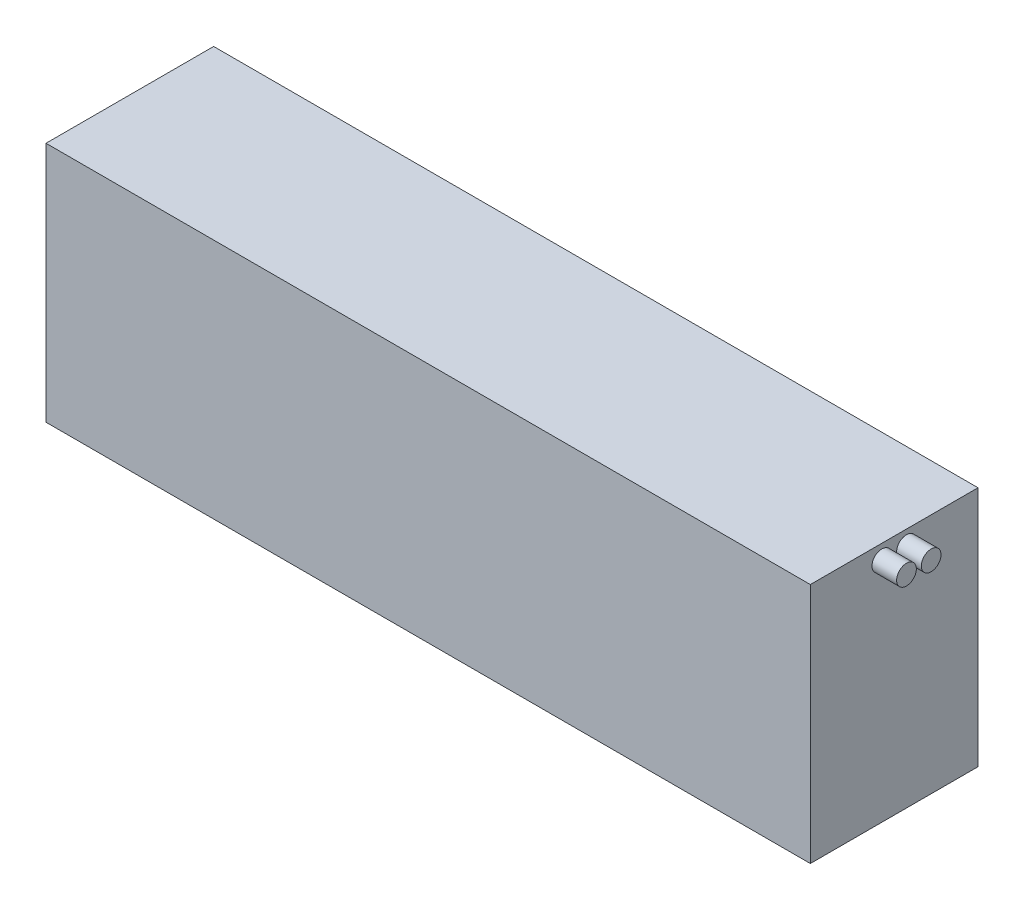
SolidWorks part; units mm, degrees
ref_plane "Plan de face" through (0, 0, 0) normal (0, 0, 1) x (1, 0, 0)
ref_plane "Plan de dessus" through (0, 0, 0) normal (0, 1, 0) x (1, 0, 0)
ref_plane "Plan de droite" through (0, 0, 0) normal (1, 0, 0) x (0, 0, -1)
sketch "Esquisse1" plane through (0, 0, 0) normal (0, 1, 0) x (1, 0, 0)
  line L1 (0, 0) -> (155, 0)
  line L2 (0, 0) -> (0, 34)
  line L3 (0, 34) -> (155, 34)
  line L4 (155, 0) -> (155, 34)
  dimension "D1" = 34
  dimension "D2" = 155
extrude "Boss.-Extru.1" add sketch "Esquisse1" along normal blind 49
sketch "Esquisse2" plane through (155, 0, 0) normal (1, 0, 0) x (0, 0, -1)
  line L0 (17, 49) -> (17, 38.0042) construction
  line L1 (0, 49) -> (34, 49) construction
  circle A0 centre (14.5, 46) radius 2
  circle A1 centre (19.5, 46) radius 2
  dimension "D1" = 3
  dimension "D2" = 4
  dimension "D3" = 5
extrude "Boss.-Extru.2" add sketch "Esquisse2" along normal blind 5
